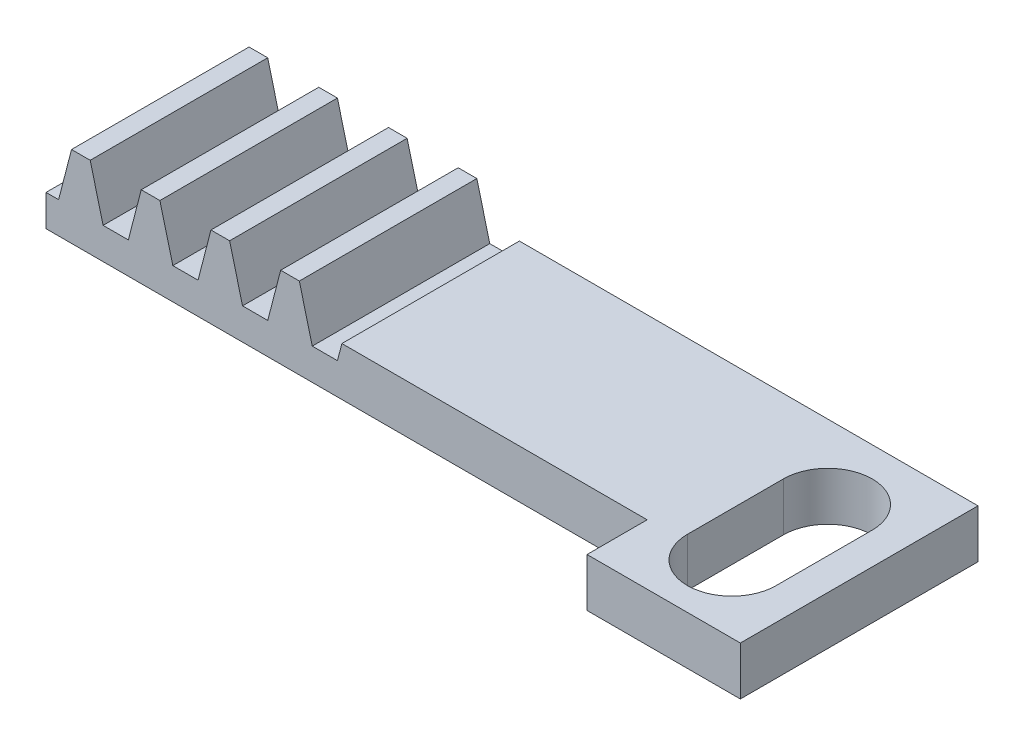
SolidWorks part; units mm, degrees
extrude "Blank" add sketch "BlankSke" against normal blind 12
sketch "BlankSke" plane through (0, 0, 0) normal (0, 0, 1) x (1, 0, 0)
  line L1 (0, 0) -> (20, 0)
  line L2 (0, 0) -> (0, 5.5)
  line L3 (0, 5.5) -> (20, 5.5)
  line L4 (20, 0) -> (20, 5.5)
  dimension "Length" = 20
  dimension "Blank_height" = 5.5
ref_plane "Plane1" through (0, 0, 0) normal (0, 0, 1) x (1, 0, 0)
ref_plane "Plane2" through (0, 0, 0) normal (0, 1, 0) x (1, 0, 0)
ref_plane "Plane3" through (0, 0, 0) normal (1, 0, 0) x (0, 0, -1)
sketch "HoldingSke" plane through (0, 0, 0) normal (0, 1, 0) x (1, 0, 0)
  line L0 (0, 0) -> (0.0928, 0.6602)
  line L1 (-15, 0) -> (100, 0) construction
  line L2 (0, 0) -> (-2.1039, 2.3779)
  line L3 (0, 0) -> (-11.863, 4.5341)
  line L4 (0, 0) -> (8.5887, 0.9027)
  line L5 (0, 0) -> (-23.7986, -8.8762)
  line L6 (0, 0) -> (-10.5278, -7.1032)
  line L9 (-67.7845, 28.3722) -> (-48.4216, 33.3798)
  line L10 (-76.2, 3.8779) -> (-72.2, 3.8779)
  line L11 (0, 0) -> (-12, 0)
  line L12 (-76.2, 101.6) -> (-76.147, 101.6)
  line L13 (24.9733, 27.94) -> (52.9518, 28.4284)
  line L14 (24.9733, 27.94) -> (24.9743, 27.94)
  line L15 (24.9733, 27.94) -> (100.4006, 29.5858)
  circle A0 centre (0, 0) radius 19.05
  circle A1 centre (0, 0) radius 2
  circle A2 centre (0, 0) radius 12.7
  dimension "MPH" = 4
  dimension "Diameter" = 38.1
  dimension "Num_teeth" = 6
  dimension "Pitch" = 0.6667
  dimension "Show_teeth" = 998
  dimension "Thickness" = 12.7
  dimension "Ap" = 14.5
  dimension "Pitch_height" = 4
  dimension "Width" = 12
  dimension "Backlash" = 0.053
  dimension "Addendum_fac" = 1
  dimension "Dedendum_fac" = 1.25
  dimension "Clearance_fac" = 0.25
  dimension "Dedendum_add" = 0.001
  dimension "Length" = 20
  dimension "Module" = 1.5
sketch "TooCutSkeIll" plane through (0, 0, 0) normal (0, 0, 1) x (1, 0, 0)
  line L0 (-1.7134, 5.455) -> (-0.9251, 2.4069)
  line L1 (-0.5611, 2.125) -> (0.5611, 2.125)
  line L2 (0.9251, 2.4069) -> (1.7134, 5.455)
  line L3 (20, 5.5) -> (0, 5.5) construction
  line L4 (0, 0) -> (0, 64.897) construction
  line L5 (-13.208, 4) -> (12.954, 4) construction
  line L6 (0, 0) -> (20, 0) construction
  line L7 (1.3371, 4) -> (1.3371, 48.7463) construction
  line L8 (-1.3371, 4) -> (-1.3371, 48.7463) construction
  line L9 (1.7715, 5.5) -> (1.7715, 5.5254)
  line L10 (-1.7715, 5.5) -> (-1.7715, 5.5254)
  line L11 (-1.7715, 5.5254) -> (1.7715, 5.5254)
  arc A0 (0.5611, 2.125) -> (0.9251, 2.4069) centre (0.5611, 2.501) ccw
  arc A1 (-0.9251, 2.4069) -> (-0.5611, 2.125) centre (-0.5611, 2.501) ccw
  arc A2 (1.7715, 5.5) -> (1.7134, 5.455) centre (1.7715, 5.44) ccw
  arc A3 (-1.7134, 5.455) -> (-1.7715, 5.5) centre (-1.7715, 5.44) ccw
  dimension "Pitch_height" = 4
  dimension "Addendum_plus" = 1.5254
  dimension "Pressure_angle" = 14.5
  dimension "Gap_width" = 2.6742
  dimension "Dedendum" = 1.875
extrude "ToothCutIll" [suppressed] cut sketch "TooCutSkeIll" against normal through all
sketch "TooCutSkeSim" plane through (0, 0, 0) normal (0, 0, 1) x (1, 0, 0)
  line L0 (0.8522, 2.125) -> (-0.8522, 2.125)
  line L1 (1.7316, 5.5254) -> (0.8522, 2.125)
  line L2 (0, 17.4625) -> (0, 53.467) construction
  line L3 (1.7316, 5.5254) -> (-1.7316, 5.5254)
  line L6 (-1.7316, 5.5254) -> (-0.8522, 2.125)
  line L9 (-1.3371, 4) -> (1.3371, 4) construction
  line L10 (0, 0) -> (20, 0) construction
  line L11 (1.3371, 4) -> (1.3371, 53.467) construction
  line L12 (-1.3371, 4) -> (-1.3371, 53.467) construction
  dimension "Pitch_height" = 4
  dimension "Addendum_plus" = 1.5254
  dimension "Pressure_angle" = 14.5
  dimension "Gap_width" = 2.6742
  dimension "Dedendum" = 1.875
extrude "ToothCutSim" cut sketch "TooCutSkeSim" against normal through all
pattern_linear "TeethCuts" count 5 spacing 4.7124 along (1, 0, 0) of "ToothCutIll", "ToothCutSim"
sketch "Sketch2" plane through (20, 0, 0) normal (1, 0, 0) x (0, 0, -1)
  line L1 (0, 3.2783) -> (12, 3.2783)
  line L2 (0, 3.2783) -> (0, 0)
  line L3 (0, 0) -> (12, 0)
  line L4 (12, 3.2783) -> (12, 0)
extrude "Boss-Extrude1" add sketch "Sketch2" along normal blind 31
sketch "Sketch3" plane through (0, 3.2783, 0) normal (0, 1, 0) x (1, 0, 0)
  line L0 (45.847, 7) -> (45.847, 5) construction
  line L1 (48.847, 7) -> (48.847, 5)
  line L2 (42.847, 7) -> (42.847, 5)
  line L4 (51, 12) -> (20, 12) construction
  arc A0 (48.847, 7) -> (42.847, 7) centre (45.847, 7) ccw
  arc A1 (42.847, 5) -> (48.847, 5) centre (45.847, 5) ccw
  point P2 (45.847, 6)
  point P7 (0, 0)
  dimension "D2" = 3
  dimension "D1" = 6
  dimension "D3" = 2
extrude "Cut-Extrude2" cut sketch "Sketch3" against normal up to next
sketch "Sketch5" plane through (0, 3.2783, 0) normal (0, 1, 0) x (1, 0, 0)
  line L0 (51, 0) -> (20, 0) construction
  line L1 (40.6368, 0) -> (42.8903, 0)
  line L2 (40.6368, 0) -> (40.6368, -4.064)
  line L3 (40.6368, -4.064) -> (51, -4.064)
  line L4 (51, 0) -> (51, -4.064)
  line L5 (45.847, 7) -> (45.847, 0.508) construction
  line L6 (48.847, 7) -> (48.847, 0.508)
  line L7 (42.847, 7) -> (42.847, 0.508)
  line L8 (51, 12) -> (51, 0) construction
  line L9 (48.8037, 0) -> (51, 0)
  arc A0 (48.847, 7) -> (42.847, 7) centre (45.847, 7) ccw
  arc A1 (42.847, 0.508) -> (48.847, 0.508) centre (45.847, 0.508) ccw
  arc A2 (48.847, 7) -> (42.847, 7) centre (45.847, 7) ccw construction
  point P8 (45.847, 3.754)
  line M6 (20, 0) -> (51, 0)
extrude "Boss-Extrude2" add sketch "Sketch5" against normal up to vertex (3.2783 mm away) contours A1 L2 L3 L4 M6 up to point (51, 0, 0)
sketch "Sketch6" plane through (0, 3.2783, 0) normal (0, 1, 0) x (1, 0, 0)
  line L0 (45.847, 7) -> (45.847, 0.508) construction
  line L1 (48.847, 7) -> (48.847, 0.508)
  line L2 (42.847, 7) -> (42.847, 0.508)
  arc A0 (48.847, 7) -> (42.847, 7) centre (45.847, 7) ccw
  arc A1 (42.847, 0.508) -> (48.847, 0.508) centre (45.847, 0.508) ccw
  arc A2 (48.847, 7) -> (42.847, 7) centre (45.847, 7) ccw construction
  arc A3 (42.8903, 0) -> (48.8037, 0) centre (45.847, 0.508) ccw construction
  point P2 (45.847, 3.754)
extrude "Cut-Extrude3" cut sketch "Sketch6" against normal blind 22.5
equation "' \"Module@HoldingSke\" = 6.35"
equation "' \"Num_teeth@HoldingSke\" = 12"
equation "' \"Ap@HoldingSke\" =  20"
equation "' \"Ap@HoldingSke\" = 20"
equation "' \"Width@HoldingSke\" = 0.25 * 25.4"
equation "' \"Show_teeth@HoldingSke\" = 500"
equation "' \"Backlash@HoldingSke\" = 0.009 * 25.4"
equation "' \"Addendum_fac@HoldingSke\" = 1.0"
equation "' \"Dedendum_fac@HoldingSke\" = 1.25"
equation "' \"Dedendum_add@HoldingSke\" = 0.00005 * 25.4"
equation "' \"Clearance_fac@HoldingSke\" = 0.25"
equation "' \"Pitch_height@HoldingSke\" = 1 * 25.4"
equation "' \"Length@HoldingSke\" = 4.71 * 25.4"
equation "\"Pitch@HoldingSke\" = 1 / \"Module@HoldingSke\""
equation "\"MPH@HoldingSke\" = \"Dedendum_fac@HoldingSke\" / \"Pitch@HoldingSke\" + 2 * \"Dedendum_add@HoldingSke\" + 0.002 * 25.4"
equation "\"MPH@HoldingSke\" = ((sgn( \"MPH@HoldingSke\" - \"Pitch_height@HoldingSke\")+1)*( \"MPH@HoldingSke\" - \"Pitch_height@HoldingSke\"))/2 + \"Pitch_height@HoldingSke\""
equation "\"Blank_height@BlankSke\" = \"Pitch_height@HoldingSke\" + \"Addendum_fac@HoldingSke\"  / \"Pitch@HoldingSke\" "
equation "\"Length@BlankSke\" =  \"Length@HoldingSke\""
equation "\"Face_width@Blank\" = \"Width@HoldingSke\""
equation "\"Pressure_angle@TooCutSkeIll\" = \"Ap@HoldingSke\""
equation "\"Addendum_plus@TooCutSkeIll\" =  \"Addendum_fac@HoldingSke\"  / \"Pitch@HoldingSke\" + 0.001 *25.4"
equation "\"Dedendum@TooCutSkeIll\" = \"Dedendum_fac@HoldingSke\"  / \"Pitch@HoldingSke\""
equation "\"Pitch_height@TooCutSkeIll\" =  \"MPH@HoldingSke\""
equation "\"Gap_width@TooCutSkeIll\" = 3.14159265 / 2 / \"Pitch@HoldingSke\" + 6 * \"Backlash@HoldingSke\""
equation "\"Pressure_angle@TooCutSkeSim\" = \"Ap@HoldingSke\""
equation "\"Addendum_plus@TooCutSkeSim\" =  \"Addendum_fac@HoldingSke\"  / \"Pitch@HoldingSke\" + 0.001 * 25.4"
equation "\"Dedendum@TooCutSkeSim\" = \"Dedendum_fac@HoldingSke\"  / \"Pitch@HoldingSke\""
equation "\"Pitch_height@TooCutSkeSim\" =  \"MPH@HoldingSke\""
equation "\"Gap_width@TooCutSkeSim\" = 3.14159265 / 2 / \"Pitch@HoldingSke\" + 6 * \"Backlash@HoldingSke\""
equation "\"Root_fillet@TooCutSkeIll\" = \"Clearance_fac@HoldingSke\" / \"Pitch@HoldingSke\" + \"Dedendum_add@HoldingSke\""
equation "\"Break_rad@TooCutSkeIll\" = 0.02 / \"Pitch@HoldingSke\" * 2"
equation "\"Linear_pitch@TeethCuts\" = 3.14159265 / \"Pitch@HoldingSke\""
equation "\"Num_teeth@HoldingSke\" = int( ( \"Length@HoldingSke\" + 0 ) / (3.14159265 / \"Pitch@HoldingSke\")) + 0.9999  + 1"
equation " \"Num_teeth@TeethCuts\" = int( \"Show_teeth@HoldingSke\" ) + 1"
equation " \"Num_teeth@TeethCuts\" = ((sgn( \"Num_teeth@TeethCuts\" - \"Num_teeth@HoldingSke\" )-1)*( \"Num_teeth@TeethCuts\" - \"Num_teeth@HoldingSke\" ))/-2+ \"Num_teeth@HoldingSke\""
equation " \"Num_teeth@TeethCuts\" = ((sgn( \"Num_teeth@TeethCuts\" - 2.0)+1)*( \"Num_teeth@TeethCuts\" - 2.0))/2 +2.0"
